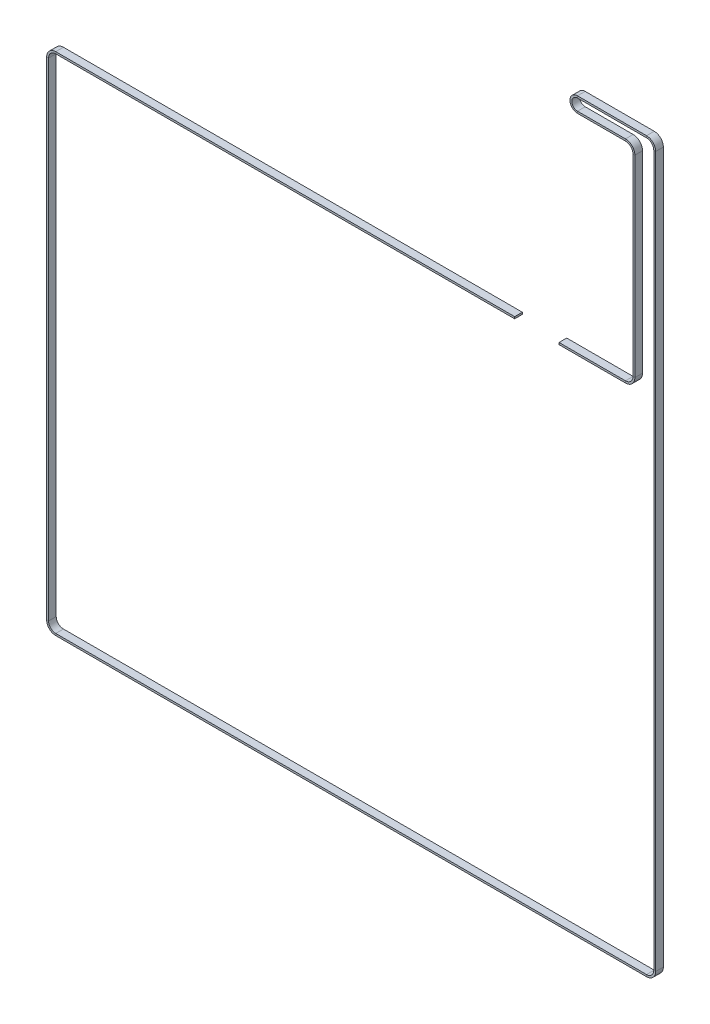
SolidWorks part; units mm, degrees
ref_plane "Front" through (0, 0, 0) normal (0, 0, 1) x (1, 0, 0)
ref_plane "Top" through (0, 0, 0) normal (0, 1, 0) x (1, 0, 0)
ref_plane "Right" through (0, 0, 0) normal (1, 0, 0) x (0, 0, -1)
sketch "Sketch1" plane through (0, 0, 0) normal (0, 0, 1) x (1, 0, 0)
  line L0 (377.3122, -142.2854) -> (431.3122, -142.2854)
  line L1 (377.3122, -152.6854) -> (414.8122, -152.6854)
  line L2 (421.4122, -159.2854) -> (421.4122, -309.9319)
  line L3 (437.6872, -148.6604) -> (437.6872, -703.9854)
  line L4 (-37.0628, -703.9854) -> (-37.0628, -322.7569)
  line L5 (431.3122, -710.3604) -> (-30.6878, -710.3604)
  line L6 (-30.6878, -316.3819) -> (328.1679, -316.3819)
  line L8 (362.8679, -316.4319) -> (362.8679, -319.9319) construction
  line L9 (414.8122, -316.5319) -> (362.8679, -316.5319)
  line L11 (328.1679, -316.4319) -> (328.1679, -319.9319) construction
  circle A0 centre (414.8122, -159.2854) radius 6.6 construction
  circle A1 centre (431.3122, -148.6604) radius 6.375 construction
  circle A2 centre (377.3122, -147.4854) radius 5.2 construction
  arc A3 (431.3122, -142.2854) -> (437.6872, -148.6604) centre (431.3122, -148.6604) cw
  arc A4 (377.3122, -152.6854) -> (377.3122, -142.2854) centre (377.3122, -147.4854) cw
  arc A5 (414.8122, -152.6854) -> (421.4122, -159.2854) centre (414.8122, -159.2854) cw
  circle A6 centre (-30.6878, -703.9854) radius 6.375 construction
  arc A7 (-30.6878, -710.3604) -> (-37.0628, -703.9854) centre (-30.6878, -703.9854) cw
  circle A8 centre (431.3122, -148.6604) radius 9 construction
  circle A9 centre (414.8122, -159.2854) radius 9 construction
  circle A10 centre (-30.6878, -322.7569) radius 6.375 construction
  circle A11 centre (431.3122, -703.9854) radius 6.375 construction
  arc A12 (437.6872, -703.9854) -> (431.3122, -710.3604) centre (431.3122, -703.9854) cw
  arc A13 (-37.0628, -322.7569) -> (-30.6878, -316.3819) centre (-30.6878, -322.7569) cw
  circle A14 centre (414.8122, -309.9319) radius 6.6 construction
  arc A15 (421.4122, -309.9319) -> (414.8122, -316.5319) centre (414.8122, -309.9319) cw
  dimension "D1" = 12.75
ref_plane "Plane1" through (328.1679, -316.3819, 0) normal (1, 0, 0) x (0, 0, -1)
sketch "Sketch4" plane through (328.1679, -316.3819, 0) normal (1, 0, 0) x (0, 0, -1)
  line L0 (0, 167.7215) -> (0, -387.6035) construction
  line L1 (3, -0.75) -> (-3, -0.75)
  line L2 (3, -0.75) -> (3, 0.75)
  line L3 (3, 0.75) -> (-3, 0.75)
  line L4 (-3, -0.75) -> (-3, 0.75)
  line L5 (3, -0.75) -> (-3, 0.75) construction
  line L6 (3, 0.75) -> (-3, -0.75) construction
  line L7 (0, 0) -> (0, -12.75) construction
  point P0 (0, 0)
  dimension "D1" = 1.5
  dimension "D2" = 6
sweep "Sweep1" add profiles "Sketch4" path "Sketch1"
